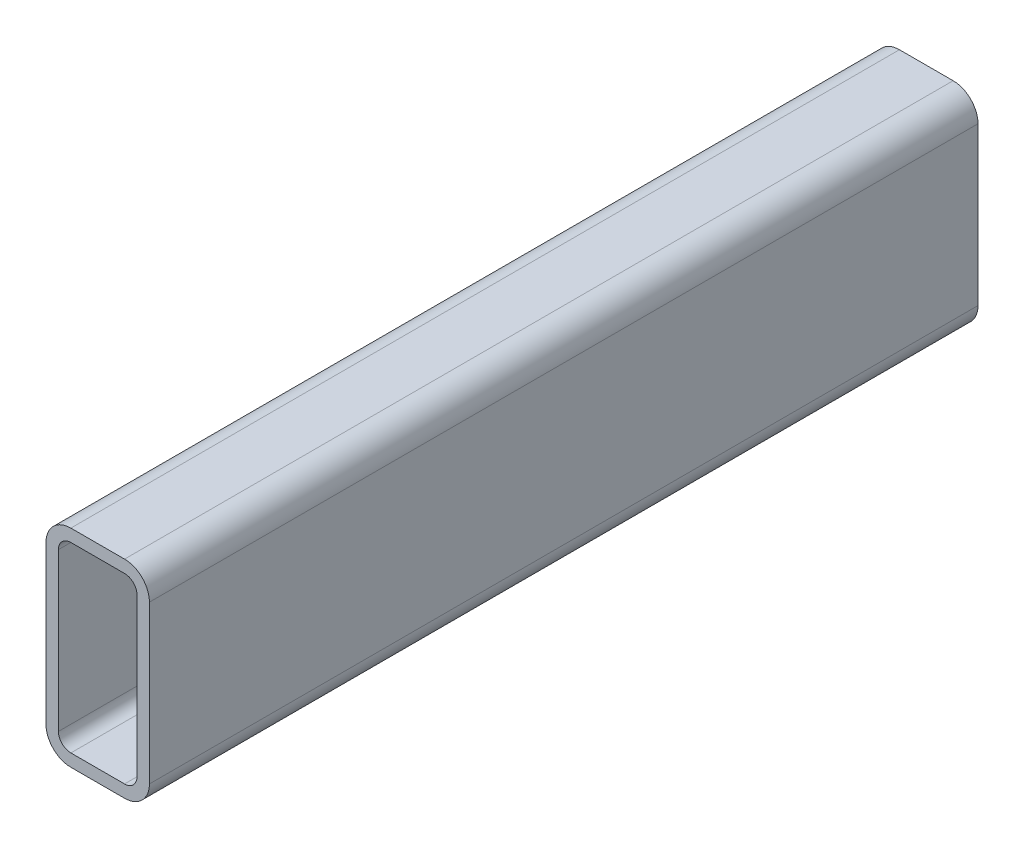
SolidWorks part; units mm, degrees
material "AISI 1020 Steel, Cold Rolled"
ref_plane "Front Plane" through (0, 0, 0) normal (0, 0, 1) x (1, 0, 0)
ref_plane "Top Plane" through (0, 0, 0) normal (0, 1, 0) x (1, 0, 0)
ref_plane "Right Plane" through (0, 0, 0) normal (1, 0, 0) x (0, 0, -1)
sketch "Sketch1" plane through (0, 0, 0) normal (0, 0, 1) x (1, 0, 0)
  line L4 (0, 44) -> (0, 6)
  line L10 (3, 44) -> (3, 6)
  line L11 (6, 47) -> (18.9612, 47)
  line L12 (21.9612, 44) -> (21.9612, 6)
  line L13 (24.9612, 44) -> (24.9612, 6)
  line L14 (6, 50) -> (18.9612, 50)
  line L15 (6, 3) -> (18.9612, 3)
  line L16 (6, 0) -> (18.9612, 0)
  arc A0 (6, 3) -> (3, 6) centre (6, 6) cw
  arc A1 (6, 0) -> (0, 6) centre (6, 6) cw
  arc A2 (18.9612, 3) -> (21.9612, 6) centre (18.9612, 6) ccw
  arc A3 (18.9612, 0) -> (24.9612, 6) centre (18.9612, 6) ccw
  arc A4 (6, 47) -> (3, 44) centre (6, 44) ccw
  arc A5 (6, 50) -> (0, 44) centre (6, 44) ccw
  arc A6 (18.9612, 47) -> (21.9612, 44) centre (18.9612, 44) cw
  arc A7 (18.9612, 50) -> (24.9612, 44) centre (18.9612, 44) cw
extrude "Boss-Extrude1" add sketch "Sketch1" along normal blind 200
